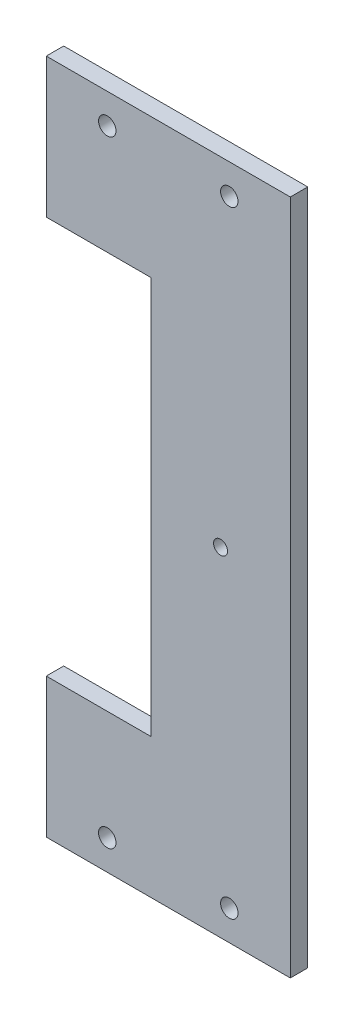
SolidWorks part; units mm, degrees
ref_plane "Front Plane" through (0, 0, 0) normal (0, 0, 1) x (1, 0, 0)
ref_plane "Top Plane" through (0, 0, 0) normal (0, 1, 0) x (1, 0, 0)
ref_plane "Right Plane" through (0, 0, 0) normal (1, 0, 0) x (0, 0, -1)
sketch "Sketch1" plane through (0, 0, 0) normal (0, 0, 1) x (1, 0, 0)
  line L0 (-24.2183, 78.115) -> (-24.2183, 38.115)
  line L1 (-24.2183, 78.115) -> (45.7817, 78.115)
  line L2 (-24.2183, 78.115) -> (-24.2183, -115.885) construction
  line L3 (-24.2183, -115.885) -> (45.7817, -115.885)
  line L4 (45.7817, 78.115) -> (45.7817, -115.885)
  line L5 (-24.2183, 38.115) -> (5.7817, 38.115)
  line L6 (5.7817, 38.115) -> (5.7817, -75.885)
  line L7 (45.7817, -18.885) -> (182.5706, -18.885) construction
  line L8 (-24.2183, -75.885) -> (5.7817, -75.885)
  line L9 (-24.2183, -115.885) -> (-24.2183, -75.885)
  line L10 (19.8782, -107.2858) -> (51.2039, -107.2858) construction
  line L11 (10.7817, -115.885) -> (10.7817, -129.1457) construction
  circle A0 centre (25.7817, -18.885) radius 2
  circle A1 centre (-6.7183, -107.2858) radius 2.5
  circle A2 centre (28.2817, -107.2858) radius 2.5
  circle A5 centre (28.2817, 69.5159) radius 2.5
  circle A6 centre (-6.7183, 69.5159) radius 2.5
  point P10 (5.7817, -18.885)
  point P21 (0, 0)
  dimension "D6" = 4
  dimension "D8" = 5
  dimension "D9" = 17.5
  dimension "D1" = 194
  dimension "D2" = 70
  dimension "D3" = 40
  dimension "D4" = 8.5992
  dimension "D5" = 30
  dimension "D7" = 20
  dimension "D10" = 35
extrude "Boss-Extrude1" add sketch "Sketch1" along normal blind 5
